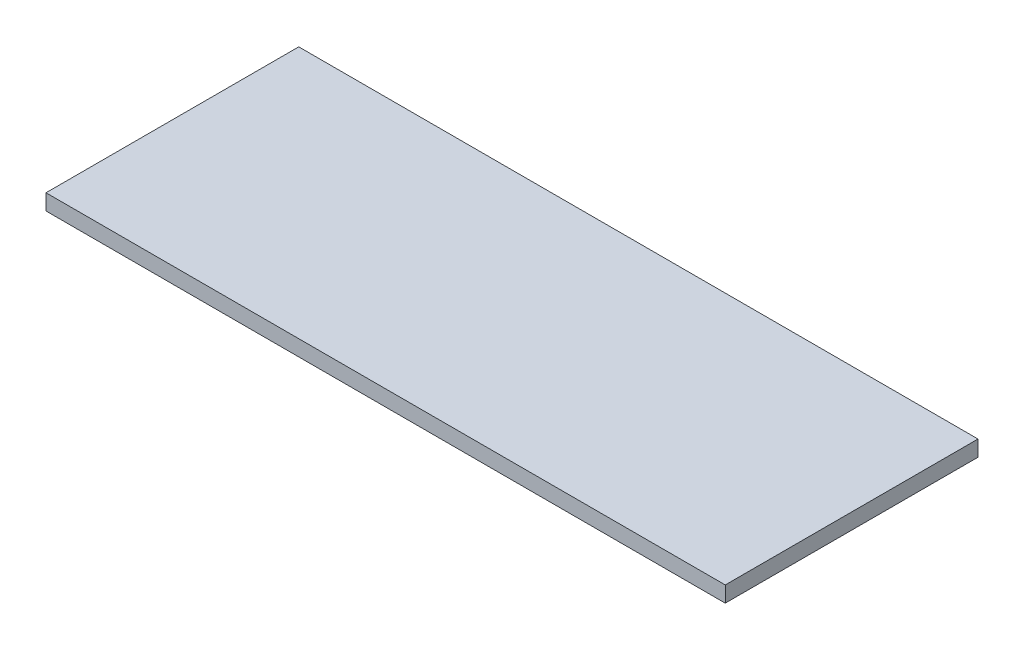
SolidWorks part; units mm, degrees
ref_plane "Front Plane" through (0, 0, 0) normal (0, 0, 1) x (1, 0, 0)
ref_plane "Top Plane" through (0, 0, 0) normal (0, 1, 0) x (1, 0, 0)
ref_plane "Right Plane" through (0, 0, 0) normal (1, 0, 0) x (0, 0, -1)
sketch "Sketch1" plane through (0, 0, 0) normal (0, 1, 0) x (1, 0, 0)
  line L1 (-64.5, 24) -> (64.5, 24)
  line L2 (-64.5, 24) -> (-64.5, -24)
  line L3 (-64.5, -24) -> (64.5, -24)
  line L4 (64.5, 24) -> (64.5, -24)
  line L5 (-64.5, 24) -> (64.5, -24) construction
  line L6 (-64.5, -24) -> (64.5, 24) construction
  point P0 (0, 0)
  dimension "D1" = 129
  dimension "D2" = 48
extrude "Boss-Extrude1" add sketch "Sketch1" along normal blind 3
